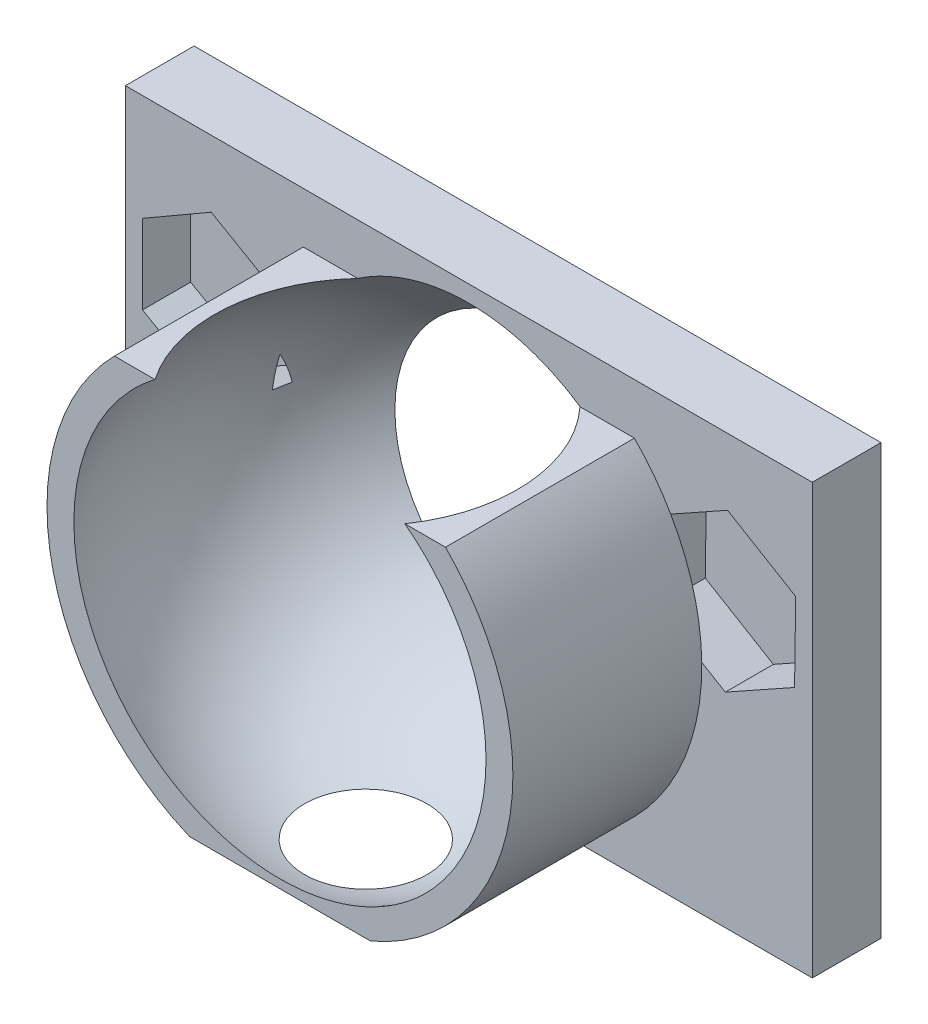
SolidWorks part; units mm, degrees
ref_plane "Alzado" through (0, 0, 0) normal (0, 0, 1) x (1, 0, 0)
ref_plane "Planta" through (0, 0, 0) normal (0, 1, 0) x (1, 0, 0)
ref_plane "Vista lateral" through (0, 0, 0) normal (1, 0, 0) x (0, 0, -1)
sketch "Croquis1" plane through (0, 0, 0) normal (0, 0, 1) x (1, 0, 0)
  line L1 (0, 0) -> (40, 0)
  line L2 (0, 0) -> (0, 25)
  line L3 (0, 25) -> (40, 25)
  line L4 (40, 0) -> (40, 25)
  dimension "D1" = 40
  dimension "D2" = 25
extrude "Saliente-Extruir2" add sketch "Croquis1" along normal blind 4
sketch "Croquis2" plane through (0, 0, 4) normal (0, 0, 1) x (1, 0, 0)
  line L1 (5, 11.8812) -> (9, 14.1906)
  line L2 (9, 14.1906) -> (9, 18.8094)
  line L3 (9, 18.8094) -> (5, 21.1188)
  line L4 (5, 21.1188) -> (1, 18.8094)
  line L5 (1, 18.8094) -> (1, 14.1906)
  line L6 (1, 14.1906) -> (5, 11.8812)
  line L8 (0, 25) -> (0, 0) construction
  line L10 (40, 25) -> (0, 25) construction
  line L11 (40, 0) -> (40, 25) construction
  line L12 (30.9673, 14.2496) -> (34.9338, 11.8831)
  line L13 (34.9338, 11.8831) -> (38.9665, 14.135)
  line L14 (38.9665, 14.135) -> (39.0327, 18.7533)
  line L15 (39.0327, 18.7533) -> (35.0662, 21.1198)
  line L16 (35.0662, 21.1198) -> (31.0335, 18.868)
  line L17 (31.0335, 18.868) -> (30.9673, 14.2496)
  circle A0 centre (5, 16.5) radius 4 construction
  circle A1 centre (35, 16.5015) radius 4 construction
  dimension "D1" = 4
  dimension "D2" = 5
  dimension "D3" = 8.5
  dimension "D4" = 4
  dimension "D5" = 5
  dimension "D6" = 8.4985
extrude "Cortar-Extruir1" cut sketch "Croquis2" against normal blind 2.8
sketch "Croquis3" plane through (0, 0, 4) normal (0, 0, 1) x (1, 0, 0)
  line L0 (20, 25) -> (20, 0) construction
  line L1 (40, 25) -> (0, 25) construction
  line L2 (0, 0) -> (40, 0) construction
  line L3 (33.5647, 12.5) -> (20, 12.5) construction
  line L5 (29.6392, 22.0439) -> (10.3608, 22.0439)
  line L6 (14.7322, 0) -> (25.2678, 0)
  circle A0 centre (20, 12.5) radius 7
  arc A1 (10.3608, 22.0439) -> (14.7322, 0) centre (20, 12.5) ccw
  arc A2 (25.2678, 0) -> (29.6392, 22.0439) centre (20, 12.5) ccw
  dimension "D1" = 14
extrude "Saliente-Extruir3" add sketch "Croquis3" along normal blind 11
ref_plane "Plano2" through (0, 0, 10) normal (0, 0, 1) x (1, 0, 0)
sketch "Croquis8" plane through (0, 0, 10) normal (0, 0, 1) x (1, 0, 0)
  line L0 (20, 19.5) -> (20, 5.5) construction
  line L1 (20, 12.5) -> (13, 12.5) construction
  line L2 (20, 25.5) -> (20, -0.5)
  circle A0 centre (20, 12.5) radius 7 construction
  circle A1 centre (20, 12.5) radius 7 construction
  arc A2 (20, 25.5) -> (20, -0.5) centre (20, 12.5) ccw
revolve "Cortar-Revolución3" cut sketch "Croquis8" angle 360 about L2
sketch "Croquis11" plane through (0, 0, 0) normal (0, 0, -1) x (-1, 0, 0)
  line L0 (-20, 25) -> (-20, 0) construction
  line L1 (-40, 25) -> (0, 25) construction
  line L2 (0, 0) -> (-40, 0) construction
  circle A0 centre (-20, 12.5) radius 8.2
extrude "Cortar-Extruir3" cut sketch "Croquis11" against normal blind 9
